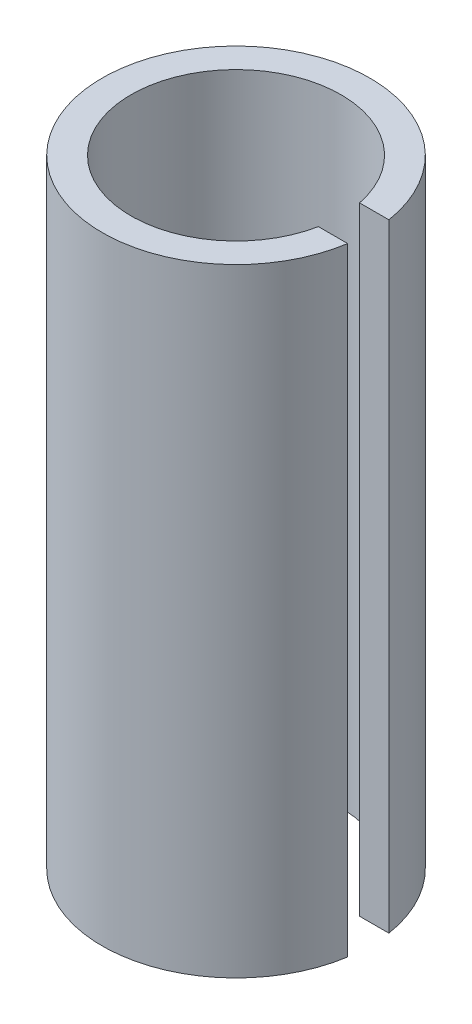
SolidWorks part; units mm, degrees
ref_plane "Front Plane" through (0, 0, 0) normal (0, 0, 1) x (1, 0, 0)
ref_plane "Top Plane" through (0, 0, 0) normal (0, 1, 0) x (1, 0, 0)
ref_plane "Right Plane" through (0, 0, 0) normal (1, 0, 0) x (0, 0, -1)
sketch "Sketch1" plane through (0, 0, 0) normal (0, 1, 0) x (1, 0, 0)
  line L0 (2.5005, 0.5) -> (3.2113, 0.5)
  line L1 (2.5005, -0.5) -> (3.2113, -0.5)
  line L2 (0, 0) -> (3.25, 0) construction
  circle A0 centre (0, 0) radius 3.25
  circle A1 centre (0, 0) radius 2.55
  dimension "D1" = 5.1
  dimension "D2" = 6.5
  dimension "D3" = 1
  dimension "D4" = 0.5
extrude "Boss-Extrude1" add sketch "Sketch1" along normal blind 15 contours A1 L0 A0 L1
